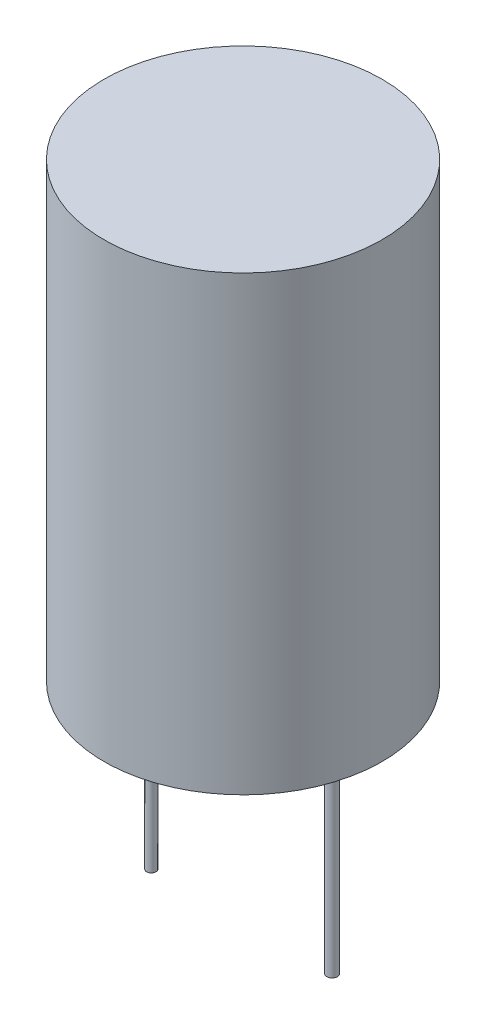
SolidWorks part; units mm, degrees
ref_plane "Front Plane" through (0, 0, 0) normal (0, 0, 1) x (1, 0, 0)
ref_plane "Top Plane" through (0, 0, 0) normal (0, 1, 0) x (1, 0, 0)
ref_plane "Right Plane" through (0, 0, 0) normal (1, 0, 0) x (0, 0, -1)
sketch "Sketch1" plane through (0, 0, 0) normal (0, 1, 0) x (1, 0, 0)
  circle A0 centre (0, 0) radius 4
  dimension "D1" = 8
extrude "Boss-Extrude1" add sketch "Sketch1" along normal blind 13
sketch "Sketch2" plane through (0, 0, 0) normal (0, -1, 0) x (1, 0, 0)
  circle A0 centre (-2.6396, 0) radius 0.1337
  circle A1 centre (2.5617, 0) radius 0.1547
extrude "Boss-Extrude2" add sketch "Sketch2" along normal blind 6
ref_plane "Plane1" through (0, 0, 0) normal (0, 0, 1) x (1, 0, 0)
ref_plane "Plane2" through (0, 0, 0) normal (1, 0, 0) x (0, 0, -1)
